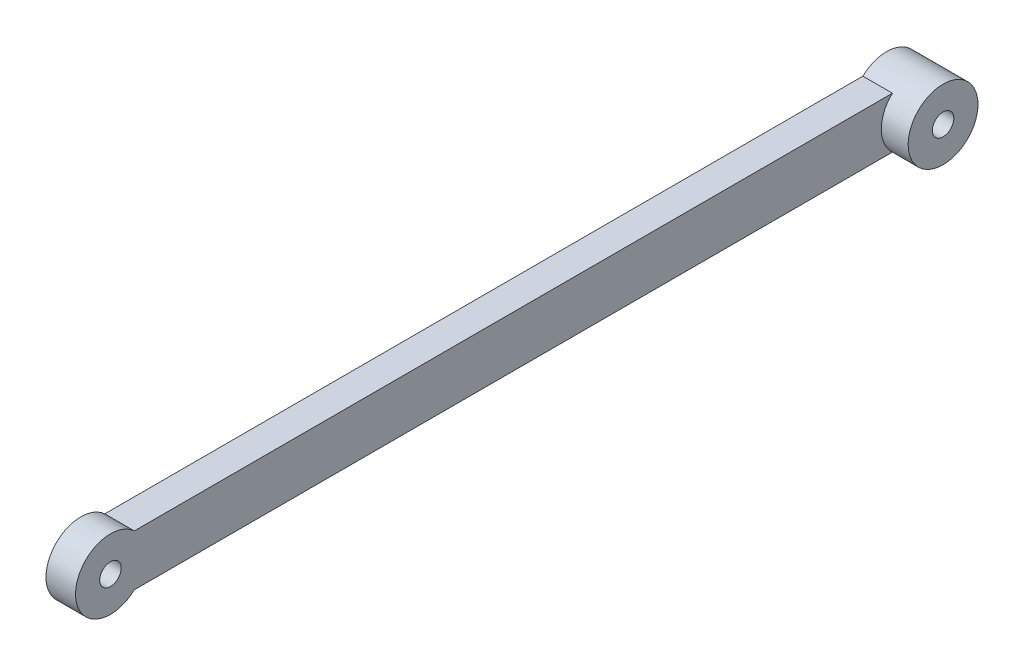
SolidWorks part; units mm, degrees
ref_plane "Plan de face" through (0, 0, 0) normal (0, 0, 1) x (1, 0, 0)
ref_plane "Plan de dessus" through (0, 0, 0) normal (0, 1, 0) x (1, 0, 0)
ref_plane "Plan de droite" through (0, 0, 0) normal (1, 0, 0) x (0, 0, -1)
sketch "Sketch1" plane through (0, 0, 0) normal (1, 0, 0) x (0, 0, -1)
  line L0 (0, 0) -> (150, 0) construction
  line L1 (4.4371, 4.75) -> (145.5629, 4.75)
  line L2 (4.4371, -4.75) -> (145.5629, -4.75)
  arc A0 (4.4371, 4.75) -> (4.4371, -4.75) centre (0, 0) ccw
  circle A1 centre (0, 0) radius 2
  arc A2 (145.5629, -4.75) -> (145.5629, 4.75) centre (150, 0) ccw
  circle A3 centre (150, 0) radius 2
  dimension "D2" = 13
  dimension "D3" = 4
  dimension "D1" = 150
  dimension "D4" = 4.75
extrude "Boss-Extrude1" add sketch "Sketch1" along normal blind 5.5
sketch "Sketch2" plane through (5.5, 0, 0) normal (1, 0, 0) x (0, 0, -1)
  circle A1 centre (150, 0) radius 6.5
  circle A2 centre (150, 0) radius 2 construction
  circle A3 centre (150, 0) radius 2
extrude "Boss-Extrude3" add sketch "Sketch2" along normal blind 5
equation "\"D4@Sketch1\"=9.5/2"
equation "\"Longueur1\"= 150mm"
equation "\"Longueur2\"= 175mm"
equation "\"D1@Sketch1\"=\"Longueur1\""
